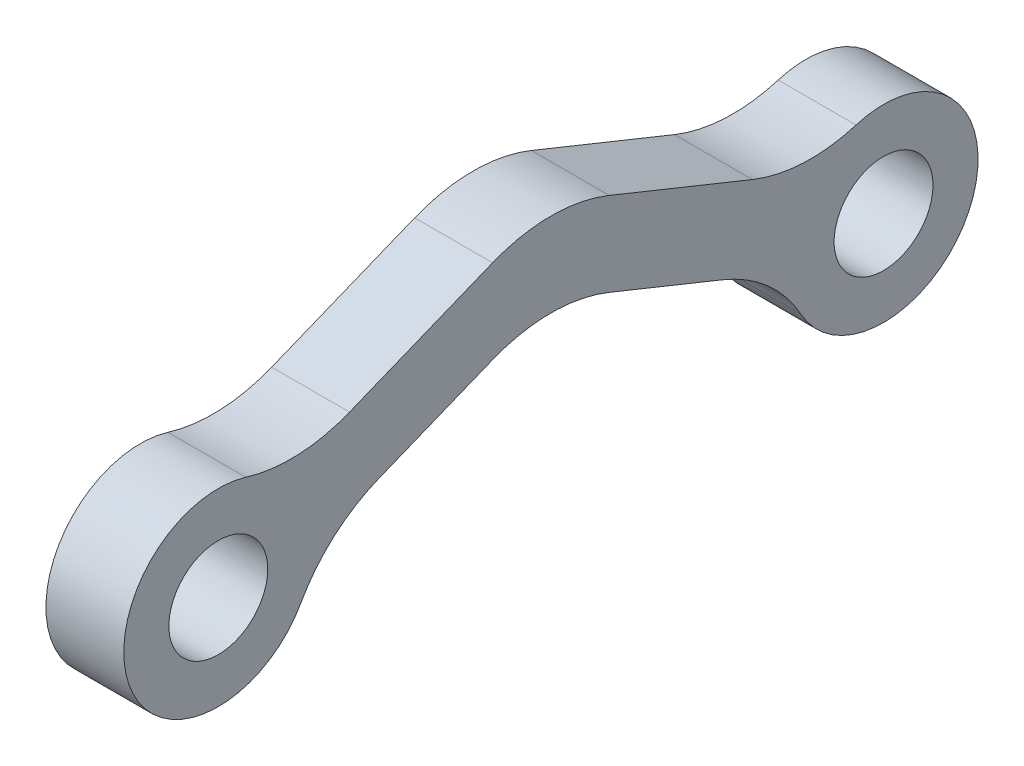
SolidWorks part; units mm, degrees
material "ABS"
ref_plane "Front Plane" through (0, 0, 0) normal (0, 0, 1) x (1, 0, 0)
ref_plane "Top Plane" through (0, 0, 0) normal (0, 1, 0) x (1, 0, 0)
ref_plane "Right Plane" through (0, 0, 0) normal (1, 0, 0) x (0, 0, -1)
sketch "Sketch1" plane through (0, 0, 0) normal (1, 0, 0) x (0, 0, -1)
  line L0 (0, 0) -> (-36.65, 0) construction
  line L1 (-34.2927, 6.1012) -> (-25.1061, 9.8128)
  line L2 (0, 0) -> (-21.36, 8.63) construction
  line L3 (-32.4196, 1.4653) -> (-25.1061, 4.4202)
  line L4 (-8.4273, 6.1012) -> (-17.6139, 9.8128)
  line L5 (-10.3004, 1.4653) -> (-17.6139, 4.4202)
  line L6 (-21.36, 11.3263) -> (-21.36, -8.5857) construction
  circle A0 centre (0, 0) radius 3.175
  arc A1 (-1.9739, -5.7401) -> (-1.9739, 5.7401) centre (0, 0) ccw construction
  arc A4 (-5.3057, -2.9487) -> (-1.7682, 5.8067) centre (0, 0) ccw
  arc A5 (-37.4143, -2.9487) -> (-40.9518, 5.8067) centre (-42.72, 0) cw
  arc A6 (-34.2927, 6.1012) -> (-40.9518, 5.8067) centre (-38.0387, 15.373) cw
  arc A7 (-32.4196, 1.4653) -> (-37.4143, -2.9487) centre (-28.6736, -7.8066) ccw
  arc A8 (-10.3004, 1.4653) -> (-5.3057, -2.9487) centre (-14.0464, -7.8066) cw
  arc A9 (-8.4273, 6.1012) -> (-1.7682, 5.8067) centre (-4.6813, 15.373) ccw
  arc A10 (-17.6139, 9.8128) -> (-25.1061, 9.8128) centre (-21.36, 0.541) ccw
  arc A11 (-17.6139, 4.4202) -> (-25.1061, 4.4202) centre (-21.36, -4.8517) ccw
  circle A12 centre (-42.72, 0) radius 3.175
  point P11 (-38.528, 4.39)
  point P20 (-36.655, -0.2459)
  point P23 (-6.065, -0.2459)
  point P26 (-4.192, 4.39)
  point P32 (-21.36, 5.9337)
  dimension "D1" = 6.35
  dimension "D2" = 6.07
  dimension "D4" = 6.35
  dimension "D5" = 2.5
  dimension "D7" = 22
  dimension "D3" = 10
  dimension "D6" = 21.36
  dimension "D8" = 22
  dimension "D9" = 21.36
  dimension "D10" = 42.72
extrude "Boss-Extrude1" add sketch "Sketch1" along normal blind 5
